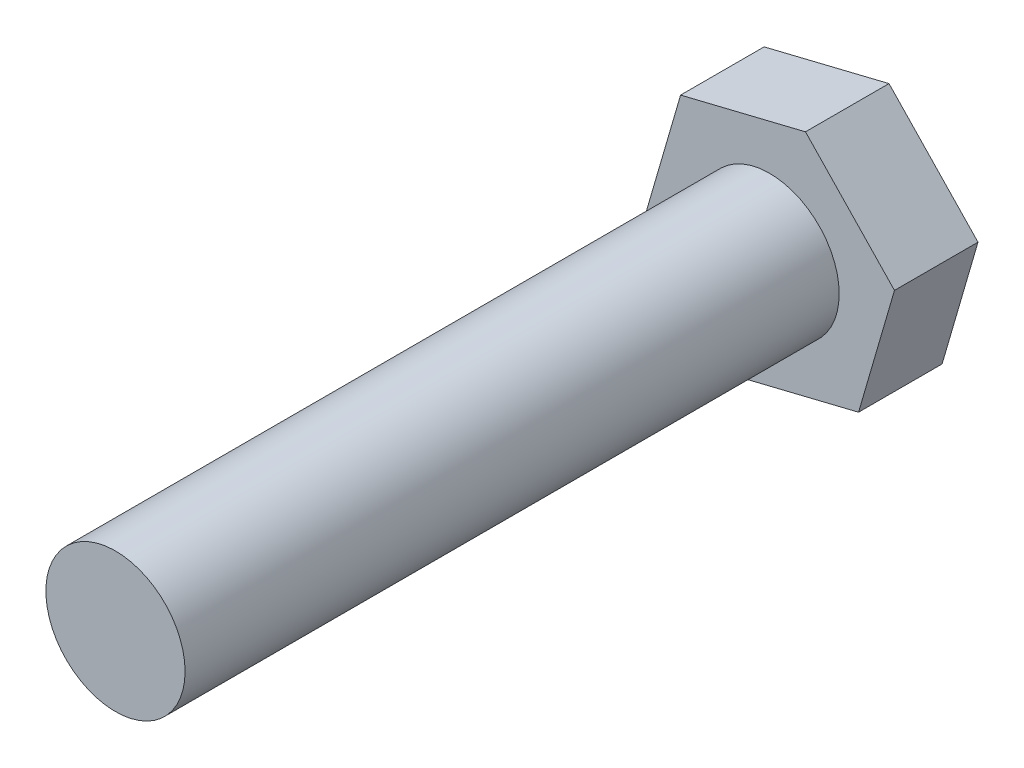
SolidWorks part; units mm, degrees
ref_plane "Front Plane" through (0, 0, 0) normal (0, 0, 1) x (1, 0, 0)
ref_plane "Top Plane" through (0, 0, 0) normal (0, 1, 0) x (1, 0, 0)
ref_plane "Right Plane" through (0, 0, 0) normal (1, 0, 0) x (0, 0, -1)
sketch "Sketch1" plane through (0, 0, 0) normal (0, 0, 1) x (1, 0, 0)
  line L1 (-3.1958, 3.3347) -> (-4.4858, -1.1003)
  line L2 (-4.4858, -1.1003) -> (-1.2901, -4.435)
  line L3 (-1.2901, -4.435) -> (3.1958, -3.3347)
  line L4 (3.1958, -3.3347) -> (4.4858, 1.1003)
  line L5 (4.4858, 1.1003) -> (1.2901, 4.435)
  line L6 (1.2901, 4.435) -> (-3.1958, 3.3347)
  circle A0 centre (0, 0) radius 4 construction
  dimension "D1" = 8
extrude "Boss-Extrude1" add sketch "Sketch1" along normal blind 3
sketch "Sketch2" plane through (0, 0, 3) normal (0, 0, 1) x (1, 0, 0)
  circle A0 centre (0, 0) radius 2.5
  dimension "D1" = 5
extrude "Boss-Extrude2" add sketch "Sketch2" along normal blind 23.492
